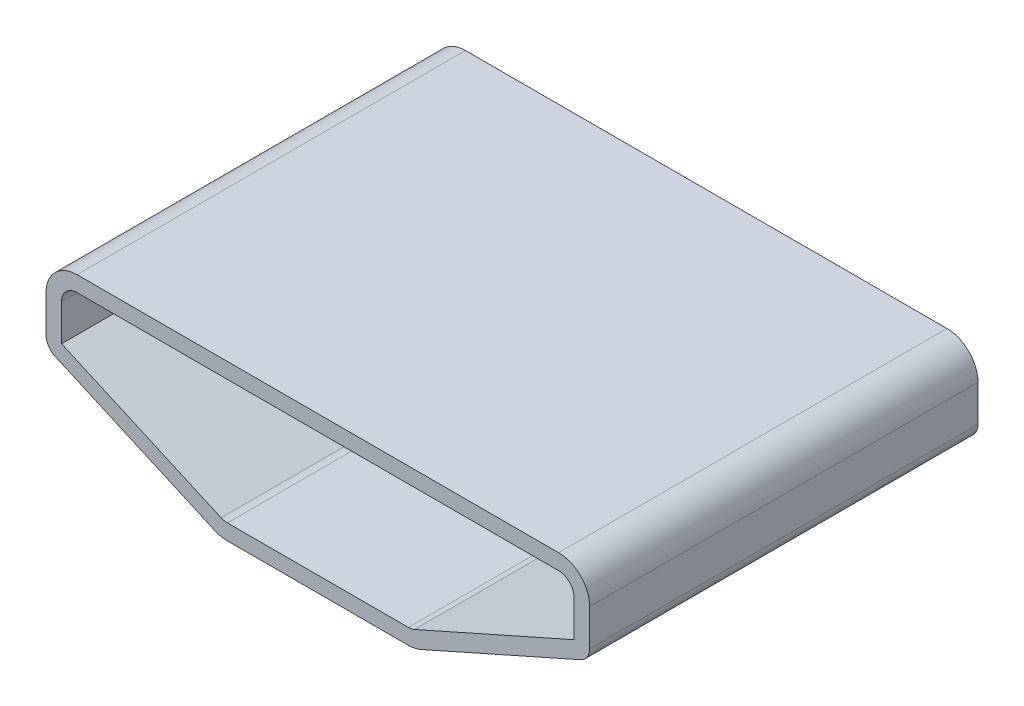
SolidWorks part; units mm, degrees
ref_plane "Front Plane" through (0, 0, 0) normal (0, 0, 1) x (1, 0, 0)
ref_plane "Top Plane" through (0, 0, 0) normal (0, 1, 0) x (1, 0, 0)
ref_plane "Right Plane" through (0, 0, 0) normal (1, 0, 0) x (0, 0, -1)
sketch "Sketch1" plane through (0, 0, 0) normal (0, 0, 1) x (1, 0, 0)
  line L0 (-2.0251, -0.5786) -> (-2.0251, -1.5786) construction
  line L1 (-3.2751, -1.5786) -> (-0.7751, -1.5786) construction
  line L3 (-5.5251, -0.4486) -> (-5.5251, 0.0214)
  line L4 (-5.1251, 0.4214) -> (1.0749, 0.4214)
  line L5 (1.4749, -0.4486) -> (1.4749, 0.0214)
  line L6 (-5.5251, -1.5786) -> (1.4749, 0.4214) construction
  line L7 (-5.5251, 0.4214) -> (1.4749, -1.5786) construction
  line L8 (1.4749, -0.5786) -> (7.2797, -0.5786) construction
  line L9 (-3.1902, -1.5786) -> (-0.86, -1.5786)
  line L10 (-0.6975, -1.5441) -> (1.3561, -0.6314)
  line L11 (-3.3527, -1.5441) -> (-5.4063, -0.6314)
  line L12 (-0.7788, -1.3614) -> (1.2749, -0.4486)
  line L13 (1.2749, -0.4486) -> (1.2749, 0.0214)
  line L14 (-5.1251, 0.2214) -> (1.0749, 0.2214)
  line L15 (-5.3251, -0.4486) -> (-5.3251, 0.0214)
  line L16 (-3.2714, -1.3614) -> (-5.3251, -0.4486)
  line L17 (-3.1902, -1.3786) -> (-0.86, -1.3786)
  arc A0 (1.4749, 0.0214) -> (1.0749, 0.4214) centre (1.0749, 0.0214) ccw
  arc A1 (-5.5251, 0.0214) -> (-5.1251, 0.4214) centre (-5.1251, 0.0214) cw
  arc A2 (1.4749, -0.4486) -> (1.3561, -0.6314) centre (1.2749, -0.4486) cw
  arc A3 (-5.5251, -0.4486) -> (-5.4063, -0.6314) centre (-5.3251, -0.4486) ccw
  arc A4 (-0.86, -1.5786) -> (-0.6975, -1.5441) centre (-0.86, -1.1786) ccw
  arc A5 (-3.1902, -1.5786) -> (-3.3527, -1.5441) centre (-3.1902, -1.1786) cw
  arc A6 (-0.86, -1.3786) -> (-0.7788, -1.3614) centre (-0.86, -1.1786) ccw
  arc A7 (1.2749, -0.4486) -> (1.2749, -0.4486) centre (1.2749, -0.4486) cw
  arc A8 (1.2749, 0.0214) -> (1.0749, 0.2214) centre (1.0749, 0.0214) ccw
  arc A9 (-5.3251, 0.0214) -> (-5.1251, 0.2214) centre (-5.1251, 0.0214) cw
  arc A10 (-5.3251, -0.4486) -> (-5.3251, -0.4486) centre (-5.3251, -0.4486) ccw
  arc A11 (-3.1902, -1.3786) -> (-3.2714, -1.3614) centre (-3.1902, -1.1786) cw
  point P11 (0, 0)
  point P12 (0, 0)
  dimension "D2" = 0.4
  dimension "D3" = 0.2
  dimension "D4" = 0.4
  dimension "D1" = 1
  dimension "D5" = 0.2
extrude "Boss-Extrude2" add sketch "Sketch1" along normal blind 5
sketch "Sketch2" plane through (0, 0, 0) normal (0, 0, 1) x (1, 0, 0)
  line L0 (-3.1902, -1.3786) -> (-0.86, -1.3786)
  line L1 (-5.4079, 0.3042) -> (1.2749, 0.3042)
  line L2 (-5.4079, 0.3042) -> (-5.4079, -0.4486)
  line L3 (-5.4079, -0.4486) -> (-5.3251, -0.4486)
  line L4 (1.2749, 0.3042) -> (1.2749, -0.4486)
  line L5 (1.2749, -0.4486) -> (-0.7788, -1.3614)
  line L6 (-5.3251, -0.4486) -> (-3.2714, -1.3614)
  arc A0 (-5.1251, 0.4214) -> (-5.5251, 0.0214) centre (-5.1251, 0.0214) ccw construction
  arc A1 (-3.2714, -1.3614) -> (-3.1902, -1.3786) centre (-3.1902, -1.1786) ccw
  arc A2 (-0.86, -1.3786) -> (-0.7788, -1.3614) centre (-0.86, -1.1786) ccw
extrude "Boss-Extrude3" add sketch "Sketch2" along normal blind 0.5
